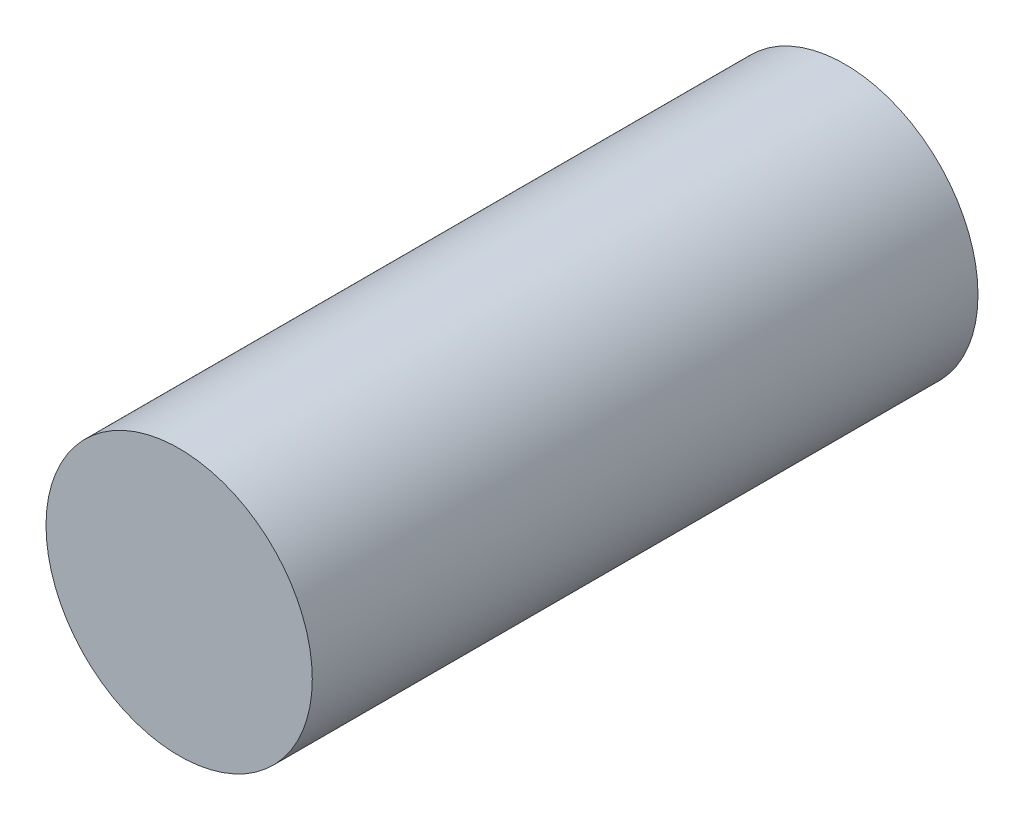
SolidWorks part; units mm, degrees
ref_plane "Front Plane" through (0, 0, 0) normal (0, 0, 1) x (1, 0, 0)
ref_plane "Top Plane" through (0, 0, 0) normal (0, 1, 0) x (1, 0, 0)
ref_plane "Right Plane" through (0, 0, 0) normal (1, 0, 0) x (0, 0, -1)
sketch "Sketch1" plane through (0, 0, 0) normal (0, 0, 1) x (1, 0, 0)
  circle A0 centre (0, 0) radius 5
  dimension "D1" = 10
extrude "Boss-Extrude1" add sketch "Sketch1" along normal mid plane 25
